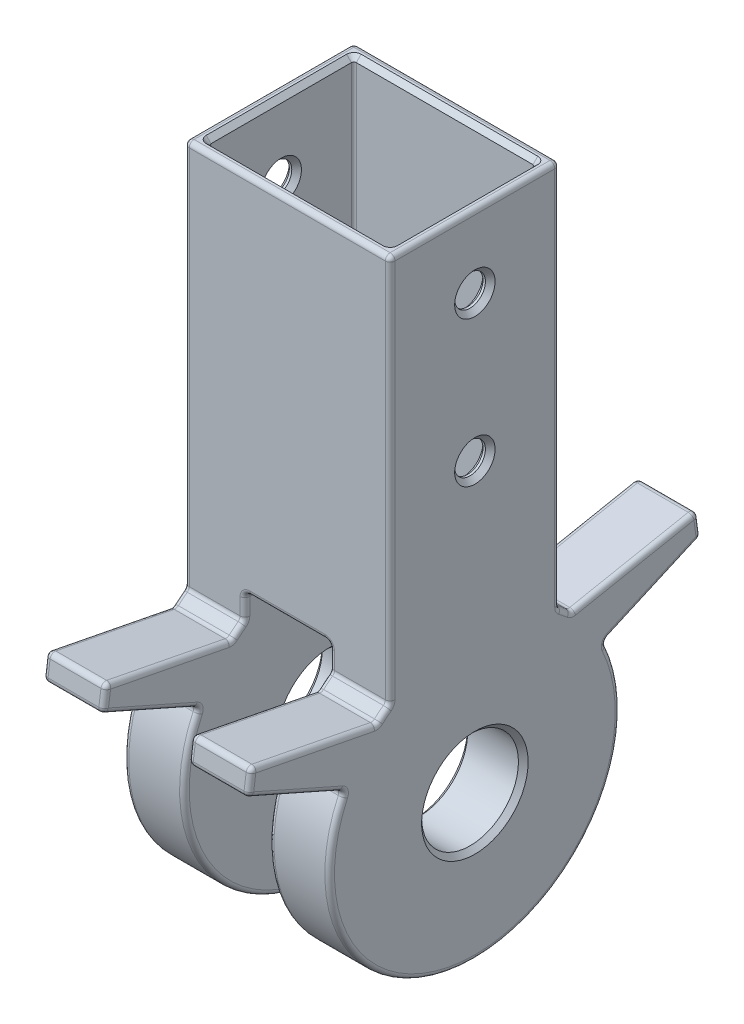
SolidWorks part; units mm, degrees
ref_plane "Front Plane" through (0, 0, 0) normal (0, 0, 1) x (1, 0, 0)
ref_plane "Top Plane" through (0, 0, 0) normal (0, 1, 0) x (1, 0, 0)
ref_plane "Right Plane" through (0, 0, 0) normal (1, 0, 0) x (0, 0, -1)
sketch "Sketch1" plane through (0, 0, 0) normal (1, 0, 0) x (0, 0, -1)
  line L0 (0, 10) -> (0, -30) construction
  line L1 (20.1105, 22.2614) -> (46.1105, 27.3451)
  line L3 (-17.5, 24.367) -> (-17.5, 104.367)
  line L4 (-17.5, 104.367) -> (17.5, 104.367)
  line L5 (17.5, 24.367) -> (17.5, 104.367)
  line L6 (46.1105, 27.3451) -> (46.7707, 22.3888)
  line L7 (46.7707, 22.3888) -> (26.7707, 13.54)
  line L8 (-46.7707, 22.3888) -> (-26.7707, 13.54)
  line L9 (-46.1105, 27.3451) -> (-46.7707, 22.3888)
  line L10 (-20.1105, 22.2614) -> (-46.1105, 27.3451)
  arc A0 (-17.5, 24.367) -> (-20.1105, 22.2614) centre (0, 0) ccw
  circle A1 centre (0, 0) radius 10
  arc A2 (20.1105, 22.2614) -> (17.5, 24.367) centre (0, 0) ccw
  arc A3 (-26.7707, 13.54) -> (26.7707, 13.54) centre (0, 0) ccw
  point P6 (-17.5, 24.367)
  point P7 (17.5, 24.367)
  dimension "D1" = 20
  dimension "D2" = 60
  dimension "D3" = 80
  dimension "D4" = 35
  dimension "D5" = 26
  dimension "D6" = 20
  dimension "D7" = 5
  dimension "D8" = 273.476
  dimension "D9" = 253.721
  dimension "D10" = 10.9736
extrude "Boss-Extrude1" add sketch "Sketch1" along normal blind 42.5
sketch "Sketch2" plane through (0, 0, 0) normal (0, 0, 1) x (1, 0, 0)
  line L0 (30, 104.367) -> (30, -45.633) construction
  line L1 (12.5, 104.367) -> (12.5, -45.633) construction
  line L2 (42.5, -55.633) -> (0, -55.633) construction
  line L3 (30, 24.367) -> (42.5, 24.367) construction
  line L4 (0, 104.367) -> (0, 24.367)
  line L5 (42.5, 104.367) -> (0, 104.367)
  line L6 (42.5, 24.367) -> (42.5, 104.367)
  line L7 (0, 24.367) -> (42.5, 24.367)
  line L8 (0, 104.367) -> (0, -55.633) construction
  line L9 (42.5, 104.367) -> (0, 104.367) construction
  line L10 (42.5, -55.633) -> (42.5, 104.367) construction
  line L12 (30, 29.367) -> (12.5, 29.367)
  line L13 (30, 29.367) -> (30, -45.633)
  line L14 (30, -45.633) -> (12.5, -45.633)
  line L15 (12.5, 29.367) -> (12.5, -45.633)
  line L19 (0, 24.367) -> (12.5, 24.367) construction
  point P10 (12.5, 29.367)
  point P12 (30, 29.367)
  dimension "D2" = 12.5
  dimension "D3" = 12.5
  dimension "D4" = 5
  dimension "D1" = 0
extrude "Cut-Extrude1" cut sketch "Sketch2" along normal blind 90 and the other way blind 90 contours L12 L15 L14 L13
sketch "Sketch3" plane through (30, 0, 0) normal (-1, 0, 0) x (0, 0, 1)
  circle A0 centre (0, 0) radius 30
  dimension "D1" = 60
extrude "Cut-Extrude2" cut sketch "Sketch3" along normal up to surface (17.5 mm away) up to face at (12.5, -10, 0)
sketch "Sketch4" plane through (42.5, 0, 0) normal (1, 0, 0) x (0, 0, -1)
  line L3 (17.5, 24.367) -> (17.5, 104.367)
  line L4 (17.5, 104.367) -> (-17.5, 104.367)
  line L5 (-17.5, 104.367) -> (-17.5, 24.367)
  line L6 (17.5, 24.367) -> (17.5, 104.367) construction
  line L7 (17.5, 104.367) -> (-17.5, 104.367) construction
  line L8 (-17.5, 104.367) -> (-17.5, 24.367) construction
  line L15 (-20.1105, 22.2614) -> (-46.1105, 27.3451)
  line L16 (-20.1105, 22.2614) -> (-46.1105, 27.3451)
  line L17 (-46.1105, 27.3451) -> (-46.7707, 22.3888)
  line L18 (-46.1105, 27.3451) -> (-46.7707, 22.3888)
  line L19 (-46.7707, 22.3888) -> (-26.7707, 13.54)
  line L20 (-46.7707, 22.3888) -> (-26.7707, 13.54)
  line L21 (26.7707, 13.54) -> (46.7707, 22.3888)
  line L22 (26.7707, 13.54) -> (46.7707, 22.3888)
  line L23 (46.7707, 22.3888) -> (46.1105, 27.3451)
  line L24 (46.7707, 22.3888) -> (46.1105, 27.3451)
  line L25 (46.1105, 27.3451) -> (20.1105, 22.2614)
  line L26 (46.1105, 27.3451) -> (20.1105, 22.2614)
  circle A0 centre (0, 59.367) radius 3.175
  circle A3 centre (0, 89.367) radius 3.175
  arc A4 (-17.5, 24.367) -> (-20.1105, 22.2614) centre (0, 0) ccw
  arc A5 (-17.5, 24.367) -> (-20.1105, 22.2614) centre (0, 0) ccw construction
  arc A8 (20.1105, 22.2614) -> (17.5, 24.367) centre (0, 0) ccw
  arc A9 (20.1105, 22.2614) -> (17.5, 24.367) centre (0, 0) ccw
  arc A10 (-26.7707, 13.54) -> (26.7707, 13.54) centre (0, 0) ccw
  arc A11 (-26.7707, 13.54) -> (26.7707, 13.54) centre (0, 0) ccw
  point P9 (0, 104.367)
  dimension "D2" = 6.35
  dimension "D3" = 30
  dimension "D4" = 15
  dimension "D1" = 0
extrude "Cut-Extrude3" cut sketch "Sketch4" against normal through all contours A3 | A0
fillet "Fillet1" radius 1 78 edges at (42.5, 23.3507, -18.8347) (30, 23.3507, -18.8347) (0, 23.3507, -18.8347) (12.5, 23.3507, -18.8347) (12.5, 23.3507, 18.8347) (0, 23.3507, 18.8347) (42.5, 23.3507, 18.8347) (30, 23.3507, 18.8347) (0, 24.8032, 33.1105) (6.25, 22.2614, 20.1105) (12.5, 24.8032, 33.1105) (36.25, 22.2614, 20.1105) (42.5, 24.8032, 33.1105) (30, 24.8032, 33.1105) (36.25, 27.3451, 46.1105) (42.5, 24.8669, 46.4406) (30, 24.8669, 46.4406) (0, 24.8669, 46.4406) (6.25, 27.3451, 46.1105) (12.5, 24.8669, 46.4406) (42.5, 24.8669, -46.4406) (30, 24.8669, -46.4406) (0, 24.8669, -46.4406) (12.5, 24.8669, -46.4406) (12.5, 29.367, 11.8151) (30, 29.367, 11.8151) (30, 29.367, -11.8151) (12.5, 29.367, -11.8151) (12.5, 30, 0) (30, 30, 0) (21.25, 29.367, 6.1303) (21.25, 29.367, -6.1303) (42.5, 17.9644, -36.7707) (36.25, 22.3888, -46.7707) (30, 17.9644, -36.7707) (36.25, 22.3888, 46.7707) (42.5, 17.9644, 36.7707) (30, 17.9644, 36.7707) (0, 17.9644, 36.7707) (6.25, 22.3888, 46.7707) (12.5, 17.9644, 36.7707) (0, 17.9644, -36.7707) (12.5, 17.9644, -36.7707) (6.25, 22.3888, -46.7707) (0, -30, 0) (6.25, 13.54, 26.7707) (12.5, -30, 0) (6.25, 13.54, -26.7707) (36.25, 13.54, 26.7707) (42.5, -30, 0) (36.25, 13.54, -26.7707) (30, -30, 0) (0, 24.8032, -33.1105) (6.25, 27.3451, -46.1105) (12.5, 24.8032, -33.1105) (6.25, 22.2614, -20.1105) (36.25, 27.3451, -46.1105) (42.5, 24.8032, -33.1105) (36.25, 22.2614, -20.1105) (30, 24.8032, -33.1105) (36.25, 24.367, -17.5) (42.5, 64.367, -17.5) (0, 64.367, -17.5) (6.25, 24.367, -17.5) (12.5, 26.867, -17.5) (21.25, 29.367, -17.5) (30, 26.867, -17.5) (21.25, 104.367, -17.5) (42.5, 104.367, 0) (0, 104.367, 0) (21.25, 29.367, 17.5) (12.5, 26.867, 17.5) (6.25, 24.367, 17.5) (0, 64.367, 17.5) (21.25, 104.367, 17.5) (42.5, 64.367, 17.5) (36.25, 24.367, 17.5) (30, 26.867, 17.5)
chamfer "Chamfer1" distance 1 angle 45 8 edges at (0, 89.367, -3.175) (0, 59.367, -3.175) (42.5, 59.367, -3.175) (42.5, 89.367, -3.175) (30, -10, 0) (12.5, -10, 0) (0, 0, -10) (42.5, 0, -10)
sketch "Sketch5" plane through (0, 104.367, 0) normal (0, 1, 0) x (1, 0, 0)
  line L8 (40, -15) -> (40, 15)
  line L9 (40, 15) -> (2.5, 15)
  line L10 (2.5, 15) -> (2.5, -15)
  line L11 (2.5, -15) -> (40, -15)
  line L12 (40, -15) -> (40, 15)
  line L13 (40, 15) -> (2.5, 15)
  line L14 (2.5, 15) -> (2.5, -15)
  line L15 (2.5, -15) -> (40, -15)
  dimension "D1" = 1.5
extrude "Cut-Extrude4" cut sketch "Sketch5" against normal blind 65
fillet "Fillet2" radius 0.5 8 edges at (2.5, 39.367, 0) (21.25, 39.367, -15) (40, 39.367, 0) (21.25, 39.367, 15) (2.5, 71.867, 15) (40, 71.867, 15) (40, 71.867, -15) (2.5, 71.867, -15)
chamfer "Chamfer2" distance 1 angle 45 12 edges at (40, 104.367, 0) (39.8536, 104.367, 14.8536) (39.8536, 104.367, -14.8536) (21.25, 104.367, 15) (2.6464, 104.367, 14.8536) (2.5, 104.367, 0) (2.6464, 104.367, -14.8536) (21.25, 104.367, -15) (2.5, 59.367, 3.175) (2.5, 89.367, 3.175) (40, 59.367, -3.175) (40, 89.367, -3.175)
